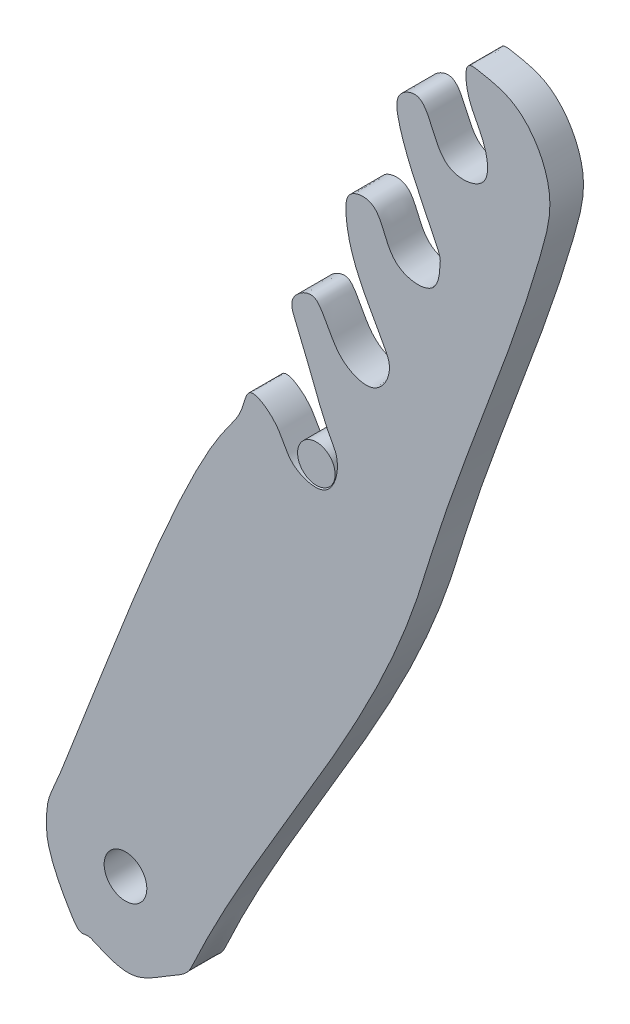
SolidWorks part; units mm, degrees
ref_plane "Front Plane" through (0, 0, 0) normal (0, 0, 1) x (1, 0, 0)
ref_plane "Top Plane" through (0, 0, 0) normal (0, 1, 0) x (1, 0, 0)
ref_plane "Right Plane" through (0, 0, 0) normal (1, 0, 0) x (0, 0, -1)
sketch "Sketch1" plane through (0, 0, 0) normal (0, 0, 1) x (1, 0, 0)
  line L0 (153.3012, 219.6765) -> (861.3141, 219.6765) construction
  line L1 (193.6847, 757.9103) -> (901.6976, 757.9103) construction
  line L2 (132.6667, 563) -> (663.3333, 563) construction
  circle A1 centre (77.431, 86.941) radius 4
  circle A2 centre (113.2014, 171.8211) radius 3.5182
  spline S0 degree 3 poles (69.1499, 72.6338) (62.8057, 82.9254) (62.2946, 91.2047) (67.2529, 100.811) (87.5353, 159.2655) (99.5977, 172.9726) (100.0577, 178.9987) (106.7001, 174.3978) (107.763, 169.0016) (116.1675, 166.4397) (117.8149, 174.0848) (114.269, 179.6785) (111.4312, 188.5143) (107.605, 196.679) (112.2902, 199.6857) (115.4522, 195.6707) (116.829, 190.7536) (124.658, 187.9343) (127.6765, 193.8538) (123.3788, 202.1466) (118.6545, 208.8221) (118.6556, 219.1797) (125.8458, 220.4036) (125.5942, 210.5187) (135.9989, 209.7198) (136.3677, 214.9392) (136.5298, 218.1228) (129.1333, 230.2088) (127.8387, 239.5612) (134.6317, 242.877) (134.7925, 230.4841) (146.0064, 231.9953) (144.886, 241.0642) (141.0338, 244.7614) (141.2397, 251.2431) (145.5622, 250.4589) (152.3971, 249.0345) (158.3154, 238.5191) (151.313, 210.7589) (139.9784, 185.8887) (124.6185, 133.4342) (102.5635, 106.3593) (89.037, 76.7289) (84.8827, 74.6676) (79.2822, 70.504) (74.3713, 72.1117) (69.5017, 74.385) (69.1499, 72.6338) (62.8057, 82.9254) (62.2946, 91.2047) knots -0.006426 -0.005032 -0.000559 0 0.011589 0.031535 0.180799 0.201843 0.223316 0.248897 0.276767 0.305437 0.337747 0.348183 0.409796 0.423219 0.44081 0.446641 0.476141 0.497606 0.519739 0.529175 0.600041 0.615013 0.627174 0.6627 0.687921 0.705245 0.709225 0.727721 0.732768 0.735476 0.746601 0.753316 0.759225 0.76916 0.772152 0.773875 0.780777 0.794743 0.804005 0.86823 0.879247 0.972315 0.973842 0.978189 0.986057 0.993574 0.994968 0.999441 1 1.011589 1.031535 1.180799 only from (67.0253, 76.0864) to (67.0253, 76.0864)
  point P13 (111.8474, 173.7541)
  point P15 (112.4641, 172.8976)
  point P17 (112.0173, 173.6465)
  point P19 (112.1653, 173.2518)
  point P21 (113.2014, 171.8211)
  dimension "D1" = 8
  dimension "D2" = 62.6191
  dimension "D3" = 67.0253
  dimension "D4" = 71.253
  dimension "D5" = 77.431
  dimension "D6" = 79.147
  dimension "D7" = 85.9755
  dimension "D8" = 89.357
  dimension "D9" = 90.0505
  dimension "D10" = 98.7128
  dimension "D11" = 100.8324
  dimension "D12" = 105.5703
  dimension "D13" = 108.7559
  dimension "D14" = 108.8744
  dimension "D15" = 109.4211
  dimension "D16" = 112.8951
  dimension "D17" = 114.0038
  dimension "D18" = 114.859
  dimension "D19" = 116.6647
  dimension "D20" = 118.4387
  dimension "D21" = 118.7846
  dimension "D22" = 119.6035
  dimension "D23" = 122.798
  dimension "D24" = 124.0562
  dimension "D25" = 125.9477
  dimension "D26" = 126.8649
  dimension "D27" = 128.3993
  dimension "D28" = 128.7074
  dimension "D29" = 129.0669
  dimension "D30" = 131.4168
  dimension "D31" = 131.9694
  dimension "D32" = 135.1773
  dimension "D33" = 135.1918
  dimension "D34" = 136.4234
  dimension "D35" = 138.0486
  dimension "D36" = 141.2828
  dimension "D37" = 141.9374
  dimension "D38" = 143.6114
  dimension "D39" = 144.523
  dimension "D40" = 144.7447
  dimension "D41" = 150.0175
  dimension "D42" = 155.6509
  dimension "D43" = 156.9177
  dimension "D44" = 71.6645
  dimension "D45" = 73.5468
  dimension "D46" = 75.1013
  dimension "D47" = 76.0864
  dimension "D48" = 77.633
  dimension "D49" = 78.944
  dimension "D50" = 86.941
  dimension "D51" = 88.8508
  dimension "D52" = 159.0704
  dimension "D53" = 168.3763
  dimension "D54" = 169.2781
  dimension "D55" = 169.5607
  dimension "D56" = 172.5531
  dimension "D57" = 174.4856
  dimension "D58" = 175.7992
  dimension "D59" = 177.1663
  dimension "D60" = 189.5473
  dimension "D61" = 190.8777
  dimension "D62" = 192.7256
  dimension "D63" = 194.7952
  dimension "D64" = 196.2735
  dimension "D65" = 197.1613
  dimension "D66" = 197.4561
  dimension "D67" = 198.5649
  dimension "D68" = 211.4693
  dimension "D69" = 211.7258
  dimension "D70" = 214.8228
  dimension "D71" = 216.4939
  dimension "D72" = 218.765
  dimension "D73" = 219.4662
  dimension "D74" = 219.6765
  dimension "D75" = 228.2329
  dimension "D76" = 232.4498
  dimension "D77" = 233.2551
  dimension "D78" = 234.9107
  dimension "D79" = 237.1424
  dimension "D80" = 238.9924
  dimension "D81" = 239.8009
  dimension "D82" = 240.9859
  dimension "D83" = 248.0033
  dimension "D84" = 248.8272
  dimension "D85" = 250.81
  dimension "D86" = 250.8363
  dimension "D87" = 563
  dimension "D88" = 757.9103
extrude "Boss-Extrude1" add sketch "Sketch1" along normal blind 6.3
